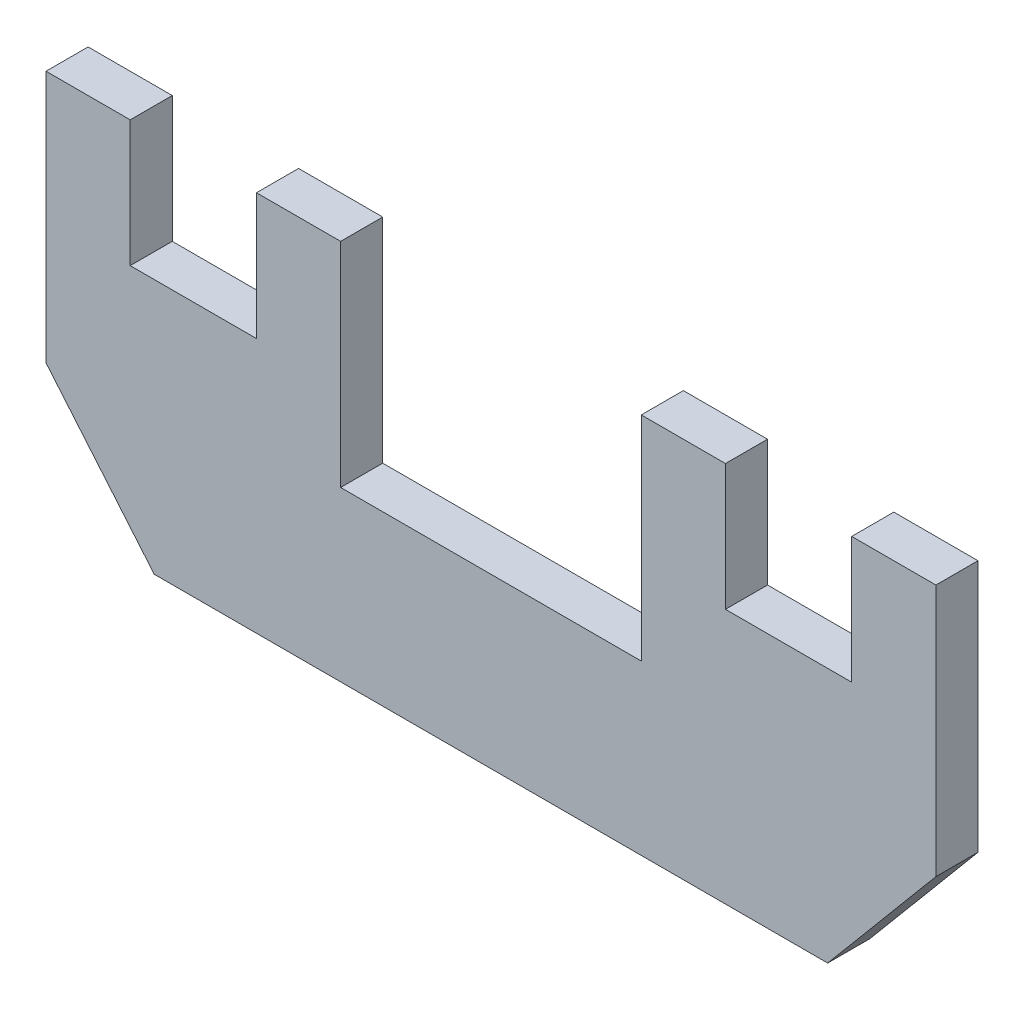
SolidWorks part; units mm, degrees
material "Cast Alloy Steel"
ref_plane "Front Plane" through (0, 0, 0) normal (0, 0, 1) x (1, 0, 0)
ref_plane "Top Plane" through (0, 0, 0) normal (0, 1, 0) x (1, 0, 0)
ref_plane "Right Plane" through (0, 0, 0) normal (1, 0, 0) x (0, 0, -1)
sketch "Sketch1" plane through (0, 0, 0) normal (0, 0, 1) x (1, 0, 0)
  line L0 (-50.8, 0) -> (50.8, 0)
  line L1 (50.8, 0) -> (67.1268, 19.4575)
  line L2 (67.1268, 19.4575) -> (67.1268, 57.5575)
  line L3 (67.1268, 57.5575) -> (54.4268, 57.5575)
  line L4 (54.4268, 57.5575) -> (54.4268, 38.5075)
  line L5 (54.4268, 38.5075) -> (35.3768, 38.5075)
  line L6 (35.3768, 38.5075) -> (35.3768, 57.5575)
  line L7 (35.3768, 57.5575) -> (22.6768, 57.5575)
  line L8 (22.6768, 57.5575) -> (22.6768, 25.4)
  line L9 (22.6768, 25.4) -> (-22.6768, 25.4)
  line L11 (-10.5266, 0) -> (136.6172, 0) construction
  line L12 (0, -27.8512) -> (0, 80.2359) construction
  line L13 (-22.6768, 57.5575) -> (-22.6768, 25.4)
  line L14 (-35.3768, 57.5575) -> (-22.6768, 57.5575)
  line L15 (-35.3768, 38.5075) -> (-35.3768, 57.5575)
  line L16 (-54.4268, 38.5075) -> (-35.3768, 38.5075)
  line L17 (-54.4268, 57.5575) -> (-54.4268, 38.5075)
  line L18 (-67.1268, 57.5575) -> (-54.4268, 57.5575)
  line L19 (-67.1268, 19.4575) -> (-67.1268, 57.5575)
  line L20 (-50.8, 0) -> (-67.1268, 19.4575)
  point P15 (0, 25.4)
  point P25 (0, 0)
  dimension "D1" = 50.8
  dimension "D2" = 25.4
  dimension "D3" = 38.1
  dimension "D4" = 12.7
  dimension "D5" = 12.7
  dimension "D6" = 19.05
  dimension "D7" = 19.05
  dimension "D8" = 19.05
  dimension "D9" = 25.4
  dimension "D10" = 50
extrude "Boss-Extrude1" add sketch "Sketch1" along normal blind 6.35
